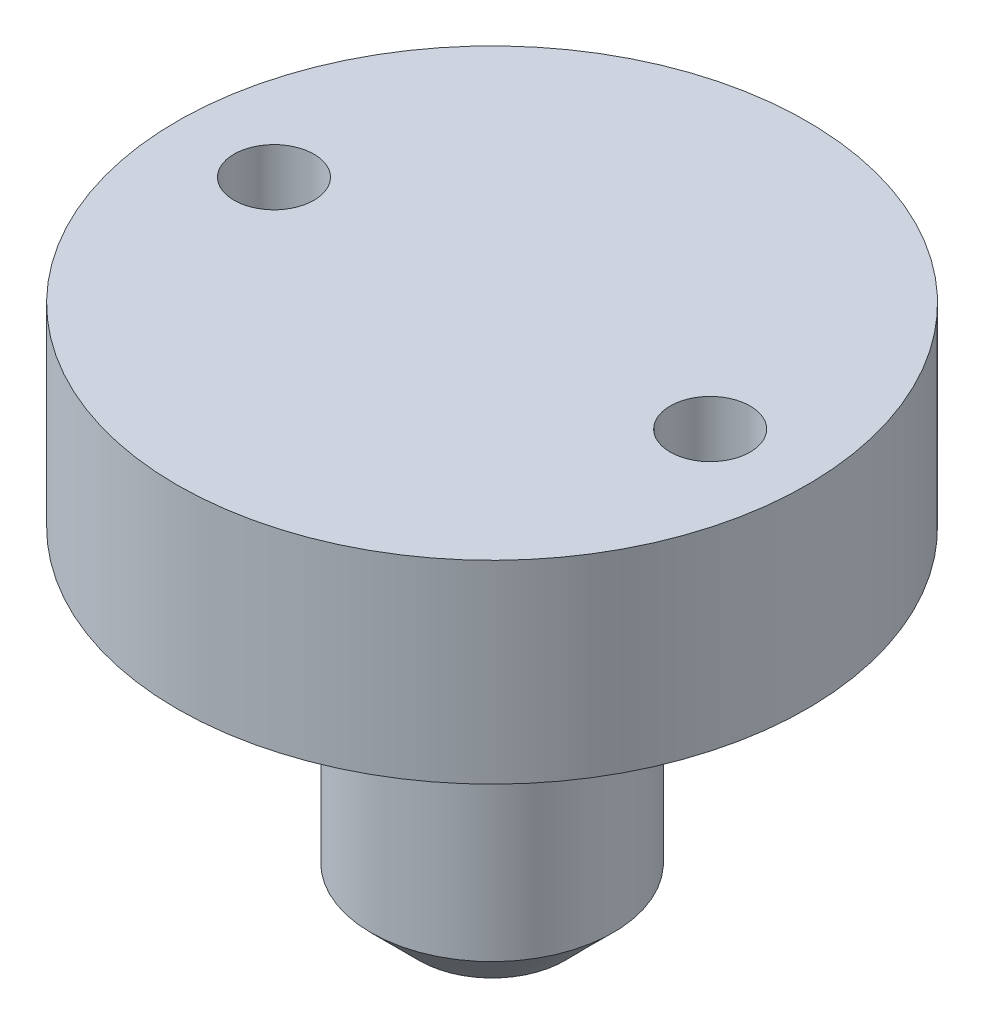
SolidWorks part; units mm, degrees
material "Q235A"
ref_plane "前视基准面" through (0, 0, 0) normal (0, 0, 1) x (1, 0, 0)
ref_plane "上视基准面" through (0, 0, 0) normal (0, 1, 0) x (1, 0, 0)
ref_plane "右视基准面" through (0, 0, 0) normal (1, 0, 0) x (0, 0, -1)
sketch "草图1" plane through (0, 0, 0) normal (0, 0, 1) x (1, 0, 0)
  line L0 (0, 60.791) -> (0, -11.4213) construction
  line L1 (0, 0) -> (5, 0)
  line L2 (5, 0) -> (5, 12)
  line L3 (5, 12) -> (4, 12)
  line L4 (4, 12) -> (4, 14)
  line L5 (4, 14) -> (13, 14)
  line L6 (13, 14) -> (13, 22)
  line L7 (13, 22) -> (0, 22)
  line L8 (0, 0) -> (0, 22)
  dimension "D1" = 26
  dimension "D2" = 8
  dimension "D3" = 10
  dimension "D4" = 22
  dimension "D5" = 14
  dimension "D6" = 2
revolve "旋转1" add sketch "草图1" angle 360 about L0
cosmetic thread "装饰螺纹线1" parameters "D1"=14, "D2"=8.917
chamfer "倒角1" distance 2 angle 45 1 edges at (0, 0, 5)
hole_wizard "M4 螺纹孔的螺纹孔钻头1" positions "草图3" profile "草图2" hole size "M4" standard "GB"
sketch "草图3" plane through (0, 22, 0) normal (0, 1, 0) x (-1, 0, 0)
  line L1 (-14.6803, 0) -> (18.3726, 0) construction
  circle A0 centre (0, 0) radius 9 construction
  point P0 (9, 0)
  point P1 (-9, 0)
  dimension "D1" = 18
sketch "草图2" plane through (-9, 22, 0) normal (1, 0, 0) x (0, 0, 1)
  line L0 (0, 0) -> (0, 4.9914)
  line L1 (0, 4.9914) -> (1.65, 4)
  line L2 (1.65, 4) -> (1.65, 0)
  line L5 (1.65, 0) -> (0, 0)
  line L10 (0, 4.9914) -> (-1.65, 4) construction
  line L11 (0, -6.35) -> (0, 107.95) construction
  dimension "孔直径" = 3.3
  dimension "孔深度" = 4
  dimension "导头角度" = 118
